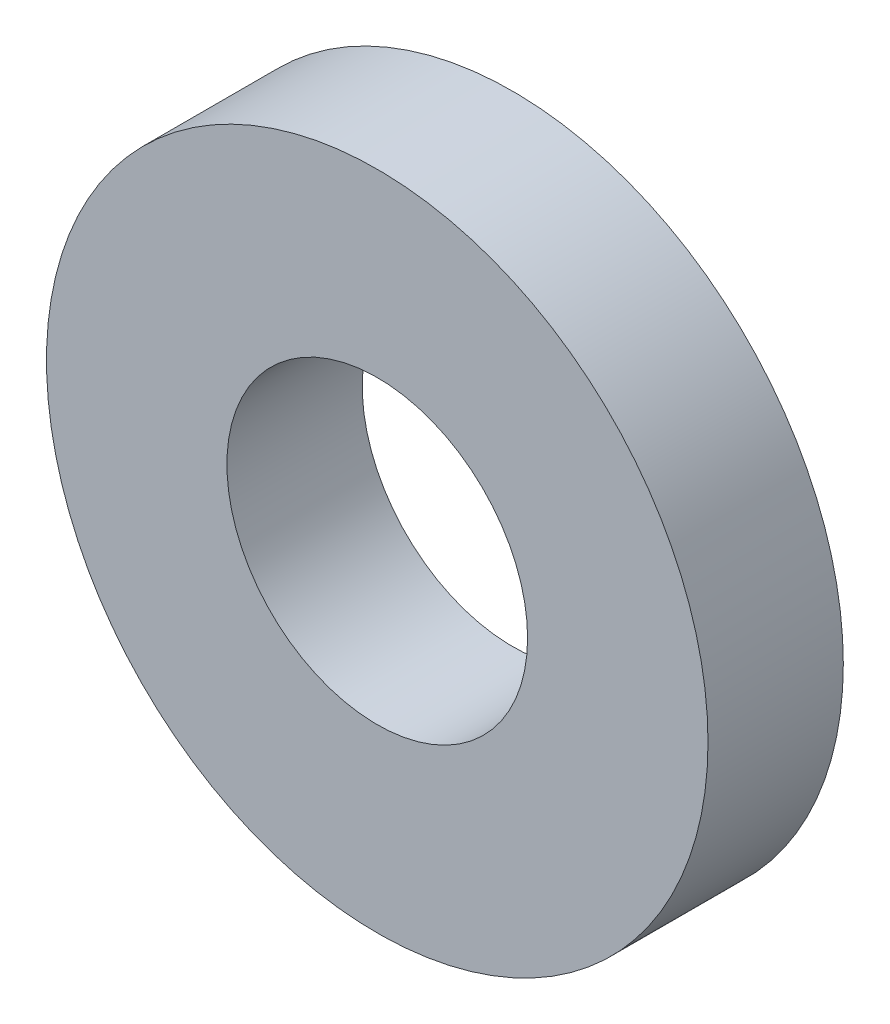
SolidWorks part; units mm, degrees
ref_plane "Front Plane" through (0, 0, 0) normal (0, 0, 1) x (1, 0, 0)
ref_plane "Top Plane" through (0, 0, 0) normal (0, 1, 0) x (1, 0, 0)
ref_plane "Right Plane" through (0, 0, 0) normal (1, 0, 0) x (0, 0, -1)
sketch "Sketch1" plane through (0, 0, 0) normal (0, 0, 1) x (1, 0, 0)
  circle A0 centre (0, 0) radius 11
  circle A1 centre (0, 0) radius 5
  dimension "D1" = 22
  dimension "D2" = 10
extrude "Boss-Extrude1" add sketch "Sketch1" along normal mid plane 4.5
